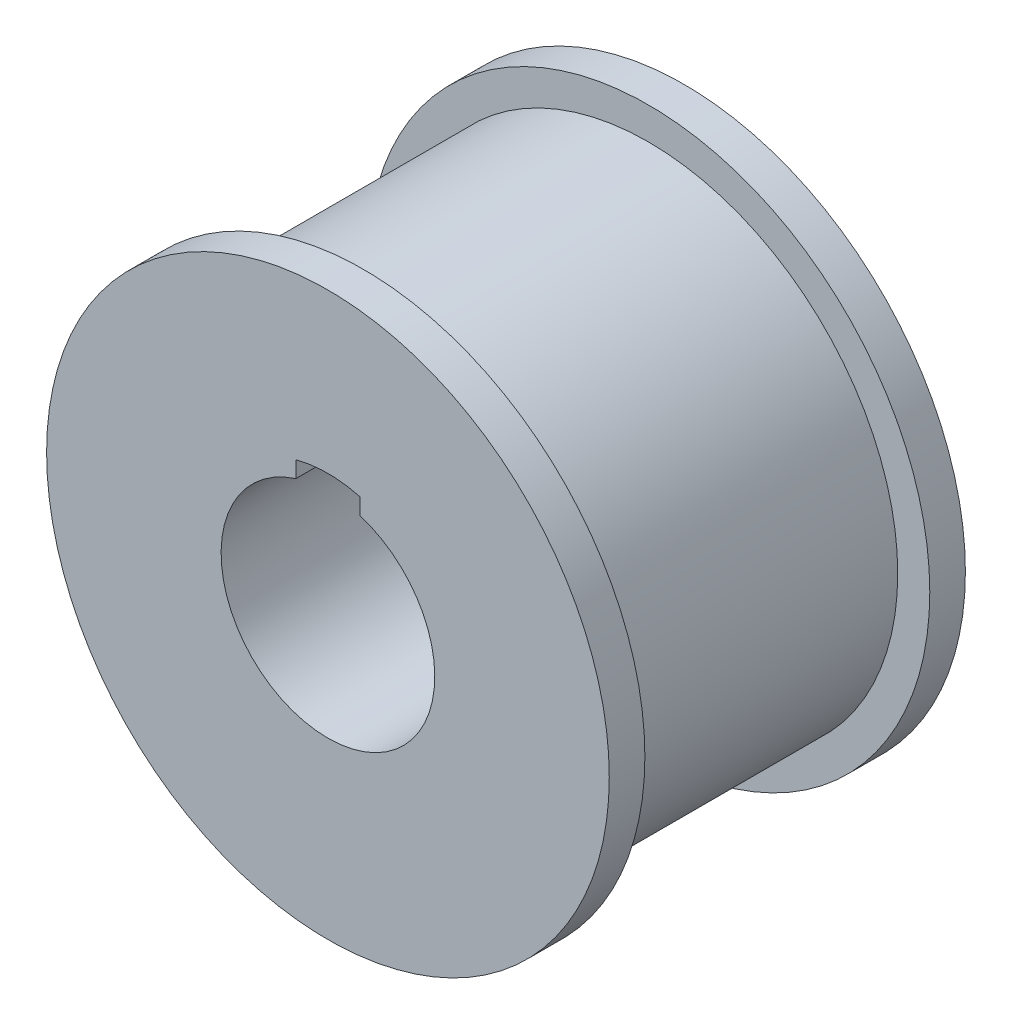
SolidWorks part; units mm, degrees
ref_plane "Front Plane" through (0, 0, 0) normal (0, 0, 1) x (1, 0, 0)
ref_plane "Top Plane" through (0, 0, 0) normal (0, 1, 0) x (1, 0, 0)
ref_plane "Right Plane" through (0, 0, 0) normal (1, 0, 0) x (0, 0, -1)
sketch "Sketch1" plane through (0, 0, 0) normal (0, 0, 1) x (1, 0, 0)
  circle A0 centre (0, 0) radius 70
  circle A1 centre (0, 0) radius 30
  dimension "D1" = 140
  dimension "D2" = 60
extrude "Boss-Extrude1" add sketch "Sketch1" along normal mid plane 80
sketch "Sketch2" plane through (0, 0, 40) normal (0, 0, 1) x (1, 0, 0)
  circle A0 centre (0, 0) radius 30 construction
  circle A1 centre (0, 0) radius 30
  circle A4 centre (0, 0) radius 79
  circle A5 centre (0, 0) radius 79
  dimension "D1" = 9
extrude "Boss-Extrude2" add sketch "Sketch2" along normal blind 10
mirror "Mirror1" about plane through (0, 0, 0) normal (0, 0, 1) of "Boss-Extrude2"
sketch "Sketch3" plane through (0, 0, 50) normal (0, 0, 1) x (1, 0, 0)
  line L0 (0, 0) -> (0, 49.1108) construction
  line L1 (9, 16.3703) -> (9, 33.2018)
  line L2 (-9, 16.3703) -> (-9, 33.2018)
  line L3 (-9, 16.3703) -> (9, 16.3703)
  line L4 (-9, 0) -> (-9, 49.1108) construction
  line L5 (9, 0) -> (9, 49.1108) construction
  circle A2 centre (0, 0) radius 34.4
  arc A3 (9, 33.2018) -> (-9, 33.2018) centre (0, 0) ccw
  point P9 (0, 0)
  dimension "D4" = 16.3703
  dimension "D1" = 9
  dimension "D2" = 9
  dimension "D3" = 4.4
extrude "Cut-Extrude1" cut sketch "Sketch3" against normal through all
